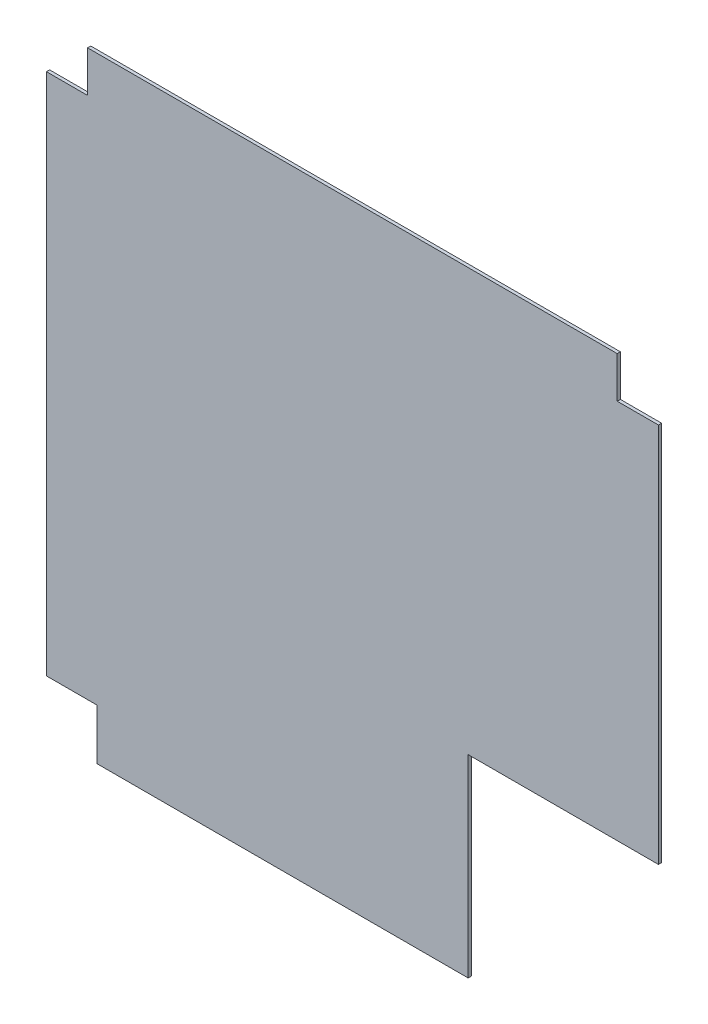
SolidWorks part; units mm, degrees
ref_plane "Front Plane" through (0, 0, 0) normal (0, 0, 1) x (1, 0, 0)
ref_plane "Top Plane" through (0, 0, 0) normal (0, 1, 0) x (1, 0, 0)
ref_plane "Right Plane" through (0, 0, 0) normal (1, 0, 0) x (0, 0, -1)
sketch "Sketch1" plane through (0, 0, 0) normal (0, 0, 1) x (1, 0, 0)
  line L1 (-371.475, -307.975) -> (371.475, -307.975)
  line L2 (-371.475, -307.975) -> (-371.475, 307.975)
  line L3 (-371.475, 307.975) -> (371.475, 307.975)
  line L4 (371.475, -307.975) -> (371.475, 307.975)
  line L5 (-371.475, -307.975) -> (371.475, 307.975) construction
  line L6 (-371.475, 307.975) -> (371.475, -307.975) construction
  point P0 (0, 0)
  dimension "D1" = 742.95
  dimension "D2" = 615.95
extrude "Boss-Extrude1" add sketch "Sketch1" along normal blind 3.175
sketch "Sketch2" plane through (0, 0, 3.175) normal (0, 0, 1) x (1, 0, 0)
  line L0 (371.475, 307.975) -> (-371.475, 307.975) construction
  line L1 (-371.475, 307.975) -> (-330.2, 307.975)
  line L2 (-371.475, 307.975) -> (-371.475, 266.7)
  line L3 (-371.475, 266.7) -> (-330.2, 266.7)
  line L4 (-330.2, 307.975) -> (-330.2, 266.7)
  line L5 (-371.475, 307.975) -> (-371.475, -307.975) construction
  line L6 (371.475, -307.975) -> (371.475, 307.975) construction
  line L7 (-371.475, -307.975) -> (-320.675, -307.975)
  line L8 (-371.475, -307.975) -> (-371.475, -257.175)
  line L9 (-371.475, -257.175) -> (-320.675, -257.175)
  line L10 (-320.675, -307.975) -> (-320.675, -257.175)
  line L11 (200.025, 307.975) -> (241.3, 307.975)
  line L12 (200.025, 307.975) -> (200.025, 266.7)
  line L13 (200.025, 266.7) -> (241.3, 266.7)
  line L14 (241.3, 307.975) -> (241.3, 266.7)
  line L15 (-371.475, -307.975) -> (371.475, -307.975) construction
  line L16 (50.8, -307.975) -> (241.3, -307.975)
  line L17 (50.8, -307.975) -> (50.8, -114.3)
  line L18 (50.8, -114.3) -> (241.3, -114.3)
  line L19 (241.3, -307.975) -> (241.3, -114.3)
  dimension "D1" = 41.275
  dimension "D2" = 41.275
  dimension "D3" = 130.175
  dimension "D4" = 41.275
  dimension "D5" = 149.225
  dimension "D6" = 193.675
  dimension "D7" = 50.8
  dimension "D8" = 50.8
extrude "Cut-Extrude1" cut sketch "Sketch2" against normal through all
sketch "Sketch3" plane through (0, 0, 3.175) normal (0, 0, 1) x (1, 0, 0)
  line L1 (371.475, 307.975) -> (241.3, 307.975)
  line L2 (371.475, 307.975) -> (371.475, -307.975)
  line L3 (371.475, -307.975) -> (241.3, -307.975)
  line L4 (241.3, 307.975) -> (241.3, -307.975)
extrude "Cut-Extrude2" cut sketch "Sketch3" against normal through all
